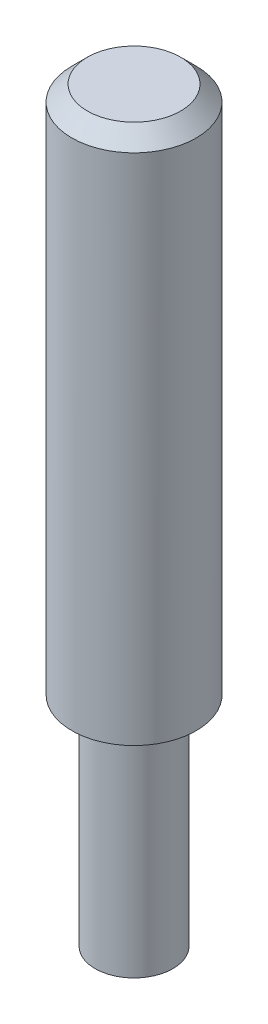
SolidWorks part; units mm, degrees
ref_plane "Front Plane" through (0, 0, 0) normal (0, 0, 1) x (1, 0, 0)
ref_plane "Top Plane" through (0, 0, 0) normal (0, 1, 0) x (1, 0, 0)
ref_plane "Right Plane" through (0, 0, 0) normal (1, 0, 0) x (0, 0, -1)
sketch "Sketch2" plane through (0, 0, 0) normal (0, 1, 0) x (1, 0, 0)
  circle A0 centre (0, 0) radius 4
  dimension "D1" = 8
extrude "Boss-Extrude1" add sketch "Sketch2" along normal mid plane 48
sketch "Sketch3" plane through (0, -24, 0) normal (0, -1, 0) x (1, 0, 0)
  circle A0 centre (0, 0) radius 2.5
  circle M2 centre (0, 0) radius 4
  dimension "D1" = 5
extrude "Cut-Extrude1" cut sketch "Sketch3" against normal blind 14 contours A0 M2
chamfer "Chamfer1" distance 1 angle 45 1 edges at (0, 24, 4)
